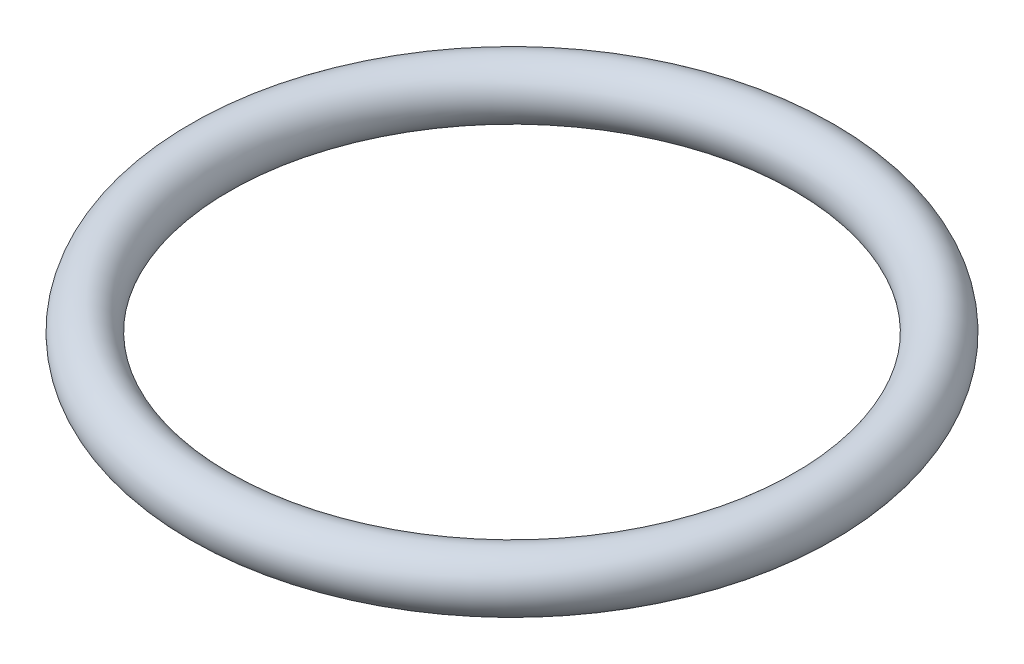
SolidWorks part; units mm, degrees
material "POLYURETHANE (11671)"
ref_plane "Front Plane" through (0, 0, 0) normal (0, 0, 1) x (1, 0, 0)
ref_plane "Top Plane" through (0, 0, 0) normal (0, 1, 0) x (1, 0, 0)
ref_plane "Right Plane" through (0, 0, 0) normal (1, 0, 0) x (0, 0, -1)
sketch "Sketch1" plane through (0, 0, 0) normal (0, 0, 1) x (1, 0, 0)
  line L0 (0, 27.3826) -> (0, -27.3826) construction
  line L1 (-7.9375, 0) -> (0, 0) construction
  circle A0 centre (-8.7312, 0) radius 0.7937
  point P4 (0, 0)
  dimension "D1" = 7.9375
  dimension "D2" = 1.5875
revolve "Revolve1" add sketch "Sketch1" angle 360 about L0
ref_plane "Plane1" through (0, 0.7937, 0) normal (0, 1, 0) x (1, 0, 0)
